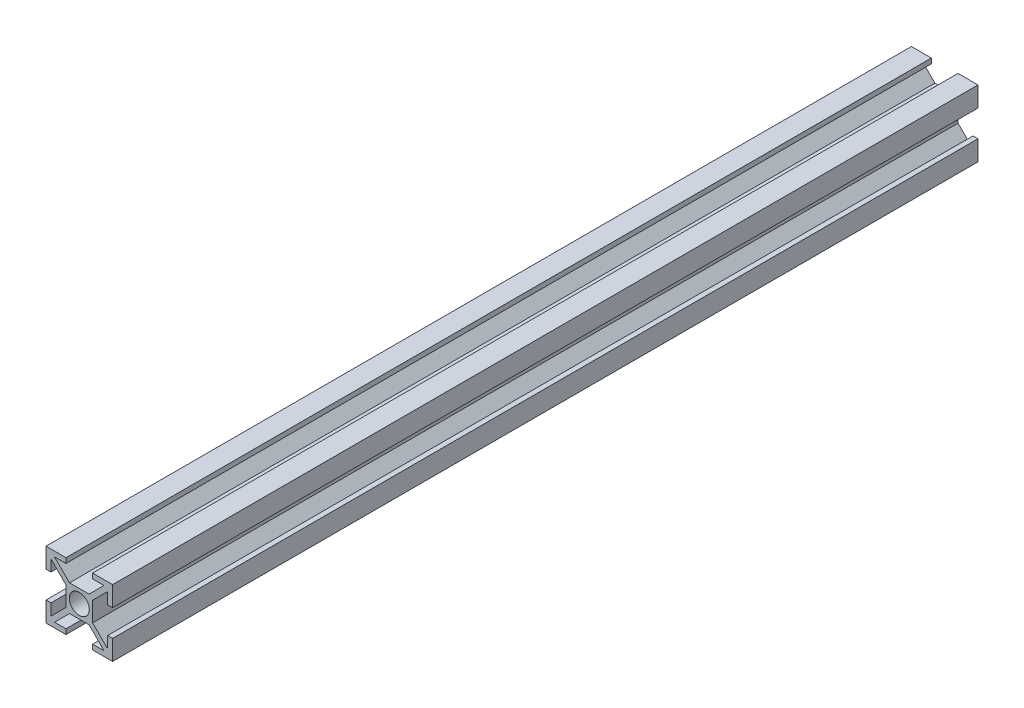
SolidWorks part; units mm, degrees
ref_plane "Plano frontal" through (0, 0, 0) normal (0, 0, 1) x (1, 0, 0)
ref_plane "Plano superior" through (0, 0, 0) normal (0, 1, 0) x (1, 0, 0)
ref_plane "Plano direito" through (0, 0, 0) normal (1, 0, 0) x (0, 0, -1)
sketch "Esboço1" plane through (0, 0, 0) normal (0, 0, 1) x (1, 0, 0)
  line L0 (-2.9393, 4) -> (2.9393, 4)
  line L1 (-10, -10) -> (-4, -10)
  line L2 (-10, -10) -> (-10, -4)
  line L3 (-10, 10) -> (-4, 10)
  line L4 (10, -10) -> (10, -4)
  line L5 (-10, -10) -> (-4, -4) construction
  line L6 (-10, 10) -> (-4, 4) construction
  line L7 (-7.4393, -8.5) -> (-2.9393, -4)
  line L8 (4, -10) -> (10, -10)
  line L9 (-8.5, -7.4393) -> (-4, -2.9393)
  line L10 (-8.5, 7.4393) -> (-4, 2.9393)
  line L11 (-7.4393, -8.5) -> (-4, -8.5)
  line L12 (-8.5, -7.4393) -> (-8.5, -4)
  line L13 (-7.4393, 8.5) -> (-4, 8.5)
  line L14 (8.5, -7.4393) -> (8.5, -4)
  line L15 (-8.5, -8.5) -> (-4, -4) construction
  line L16 (-8.5, 8.5) -> (-4, 4) construction
  line L17 (-4, 10) -> (-4, 8.5)
  line L18 (4, -8.5) -> (7.4393, -8.5)
  line L19 (-10, -4) -> (-8.5, -4)
  line L20 (4, 10) -> (4, 8.5)
  line L21 (-10, 4) -> (-8.5, 4)
  line L22 (-4, 2.9393) -> (-4, -2.9393)
  line L23 (-4, -8.5) -> (-4, -10)
  line L24 (-8.5, 4) -> (-8.5, 7.4393)
  line L25 (-10, 4) -> (-10, 10)
  line L26 (-7.4393, 8.5) -> (-2.9393, 4)
  line L27 (4, 8.5) -> (7.4393, 8.5)
  line L28 (-2.9393, -4) -> (2.9393, -4)
  line L29 (4, 10) -> (10, 10)
  line L30 (4, -8.5) -> (4, -10)
  line L31 (10, 4) -> (10, 10)
  line L32 (8.5, 4) -> (8.5, 7.4393)
  line L33 (-10.5303, -9.4697) -> (9.4697, 10.5303) construction
  line L34 (8.5, 4) -> (10, 4)
  line L35 (8.5, -4) -> (10, -4)
  line L36 (-10, -10) -> (10, 10) construction
  line L37 (4, 2.9393) -> (4, -2.9393)
  line L38 (-9.4697, -10.5303) -> (10.5303, 9.4697) construction
  line L40 (2.9393, -4) -> (7.4393, -8.5)
  line L41 (4, -4) -> (10, -10) construction
  line L42 (4, -4) -> (8.5, -8.5) construction
  line L43 (4, -2.9393) -> (8.5, -7.4393)
  line L44 (4, 0) -> (10, 0) construction
  line L45 (4, 2.9393) -> (8.5, 7.4393)
  line L46 (4, 4) -> (8.5, 8.5) construction
  line L47 (4, 4) -> (10, 10) construction
  line L48 (2.9393, 4) -> (7.4393, 8.5)
  circle A0 centre (0, 0) radius 3
  point P0 (0, 0)
  point P14 (0, 0)
  dimension "D1" = 0.75
  dimension "D3" = 1.5
  dimension "D4" = 20
  dimension "D2" = 0.75
extrude "Ressalto-extrusão1" add sketch "Esboço1" along normal blind 260
